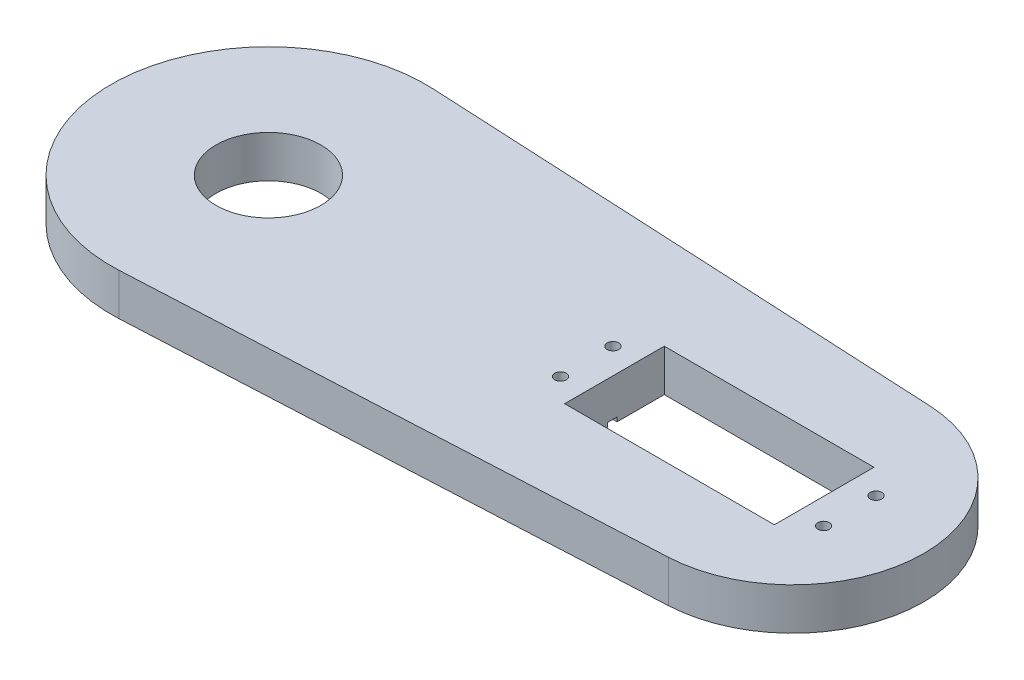
SolidWorks part; units mm, degrees
material "Haya"
ref_plane "Alzado" through (0, 0, 0) normal (0, 0, 1) x (1, 0, 0)
ref_plane "Planta" through (0, 0, 0) normal (0, 1, 0) x (1, 0, 0)
ref_plane "Vista lateral" through (0, 0, 0) normal (1, 0, 0) x (0, 0, -1)
sketch "Croquis1" plane through (0, 0, 0) normal (0, 1, 0) x (1, 0, 0)
  line L0 (1.5, 29.9625) -> (101.25, 24.9687)
  line L1 (1.5, -29.9625) -> (101.25, -24.9687)
  line L2 (66, -9.5) -> (106, -9.5)
  line L3 (66, -9.5) -> (66, 9.5)
  line L4 (106, -9.5) -> (106, 9.5)
  line L5 (66, 9.5) -> (106, 9.5)
  line L6 (66, -9.5) -> (106, 9.5) construction
  line L7 (106, -9.5) -> (66, 9.5) construction
  arc A0 (1.5, 29.9625) -> (1.5, -29.9625) centre (0, 0) ccw
  arc A1 (101.25, -24.9687) -> (101.25, 24.9687) centre (100, 0) ccw
  circle A2 centre (110.89, 5) radius 1.1
  circle A3 centre (110.89, -5) radius 1.1
  circle A4 centre (61.1116, -5.4) radius 1.1
  circle A5 centre (61.1116, 4.6) radius 1.1
  circle A6 centre (7.5, 0) radius 0.8
  circle A8 centre (0, -7.5) radius 0.8
  circle A9 centre (-7.5, 0) radius 0.8
  circle A10 centre (0, 7.5) radius 0.8
  circle A11 centre (0, 0) radius 0.8
  point P4 (86, 0)
  point P31 (0, 0)
  dimension "D1" = 60
  dimension "D2" = 50
  dimension "D7" = 2.2
  dimension "D12" = 2.2
  dimension "D13" = 2.2
  dimension "D14" = 2.2
  dimension "D17" = 1.6
  dimension "D18" = 4
  dimension "D20" = 1.6
  dimension "D3" = 100
  dimension "D4" = 6
  dimension "D5" = 40
  dimension "D6" = 19
  dimension "D8" = 4.5
  dimension "D9" = 4.89
  dimension "D10" = 10
  dimension "D11" = 49.78
  dimension "D15" = 4.9
  dimension "D16" = 10
  dimension "D19" = 7.5
extrude "Saliente-Extruir1" add sketch "Croquis1" along normal blind 8
sketch "Croquis2" plane through (0, 0, 0) normal (0, -1, 0) x (1, 0, 0)
  circle A0 centre (0, 0) radius 10
  dimension "D1" = 20
sketch "Croquis3" plane through (0, 0, 0) normal (0, -1, 0) x (1, 0, 0)
  line L0 (59, 1.3) -> (66, 1.3)
  line L1 (66, 1.3) -> (66, -0.5)
  line L2 (66, -0.5) -> (59, -0.5)
  line L3 (59, -0.5) -> (59, 1.3)
  line L4 (66, -9.5) -> (66, 9.5) construction
  line L5 (86, 9.5) -> (86, -9.5) construction
  line L6 (66, 9.5) -> (106, 9.5) construction
  line L7 (106, -9.5) -> (66, -9.5) construction
  line L8 (113, -0.5) -> (113, 1.3)
  line L9 (106, -0.5) -> (113, -0.5)
  line L10 (106, 1.3) -> (106, -0.5)
  line L11 (113, 1.3) -> (106, 1.3)
  circle A0 centre (61.1116, 5.4) radius 1.1 construction
  dimension "D3" = 4.1
  dimension "D4" = 0
  dimension "D1" = 1.8
  dimension "D2" = 7
extrude "Cortar-Extruir2" cut sketch "Croquis3" against normal blind 0.8
extrude "Cortar-Extruir4" cut sketch "Croquis2" against normal through all
